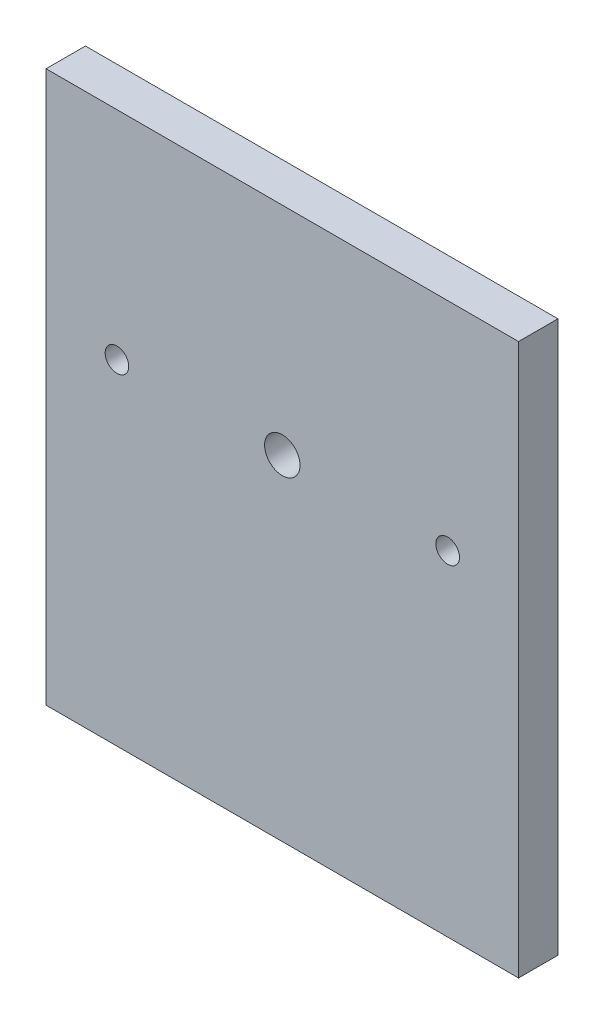
SolidWorks part; units mm, degrees
ref_plane "Front Plane" through (0, 0, 0) normal (0, 0, 1) x (1, 0, 0)
ref_plane "Top Plane" through (0, 0, 0) normal (0, 1, 0) x (1, 0, 0)
ref_plane "Right Plane" through (0, 0, 0) normal (1, 0, 0) x (0, 0, -1)
sketch "Sketch1" plane through (0, 0, 0) normal (0, 0, 1) x (1, 0, 0)
  line L1 (0, 0) -> (-120, 0)
  line L2 (0, 0) -> (0, -140)
  line L3 (0, -140) -> (-120, -140)
  line L4 (-120, 0) -> (-120, -140)
  circle A0 centre (-60, -55) radius 4.5
  circle A1 centre (-102, -55) radius 3
  circle A2 centre (-18, -55) radius 3
  dimension "D3" = 9
  dimension "D5" = 55
  dimension "D6" = 6
  dimension "D7" = 6
  dimension "D8" = 55
  dimension "D9" = 55
  dimension "D10" = 84
  dimension "D11" = 42
  dimension "D1" = 120
  dimension "D2" = 140
  dimension "D4" = 60
extrude "Boss-Extrude1" add sketch "Sketch1" along normal blind 10
